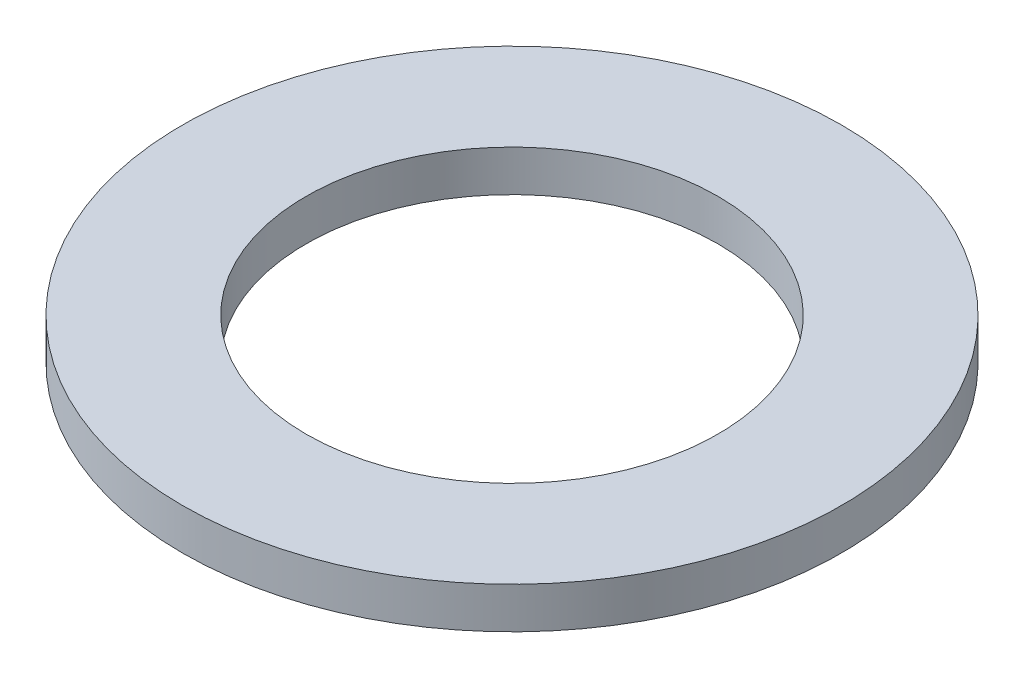
SolidWorks part; units mm, degrees
ref_plane "Front Plane" through (0, 0, 0) normal (0, 0, 1) x (1, 0, 0)
ref_plane "Top Plane" through (0, 0, 0) normal (0, 1, 0) x (1, 0, 0)
ref_plane "Right Plane" through (0, 0, 0) normal (1, 0, 0) x (0, 0, -1)
sketch "Sketch1" plane through (0, 0, 0) normal (0, 1, 0) x (1, 0, 0)
  circle A0 centre (0, 0) radius 2.5
  circle A1 centre (0, 0) radius 4
  dimension "D1" = 5
  dimension "D2" = 8
extrude "Boss-Extrude1" add sketch "Sketch1" along normal blind 0.5
